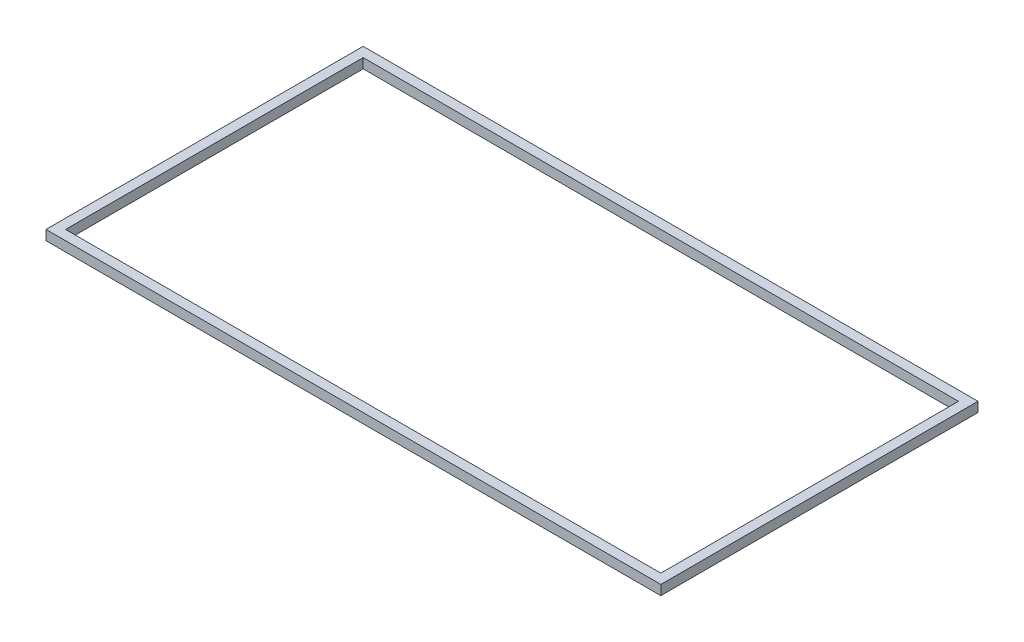
SolidWorks part; units mm, degrees
ref_plane "Front Plane" through (0, 0, 0) normal (0, 0, 1) x (1, 0, 0)
ref_plane "Top Plane" through (0, 0, 0) normal (0, 1, 0) x (1, 0, 0)
ref_plane "Right Plane" through (0, 0, 0) normal (1, 0, 0) x (0, 0, -1)
sketch "Sketch2" plane through (0, 0, 0) normal (0, 1, 0) x (1, 0, 0)
  line L1 (-304.8, -152.4) -> (304.8, -152.4)
  line L2 (-304.8, -152.4) -> (-304.8, 152.4)
  line L3 (-304.8, 152.4) -> (304.8, 152.4)
  line L4 (304.8, -152.4) -> (304.8, 152.4)
  line L5 (-304.8, -152.4) -> (304.8, 152.4) construction
  line L6 (-304.8, 152.4) -> (304.8, -152.4) construction
  point P0 (0, 0)
  dimension "D1" = 609.6
  dimension "D2" = 304.8
extrude "Extrude-Thin1" add sketch "Sketch2" along normal blind 10 thin
